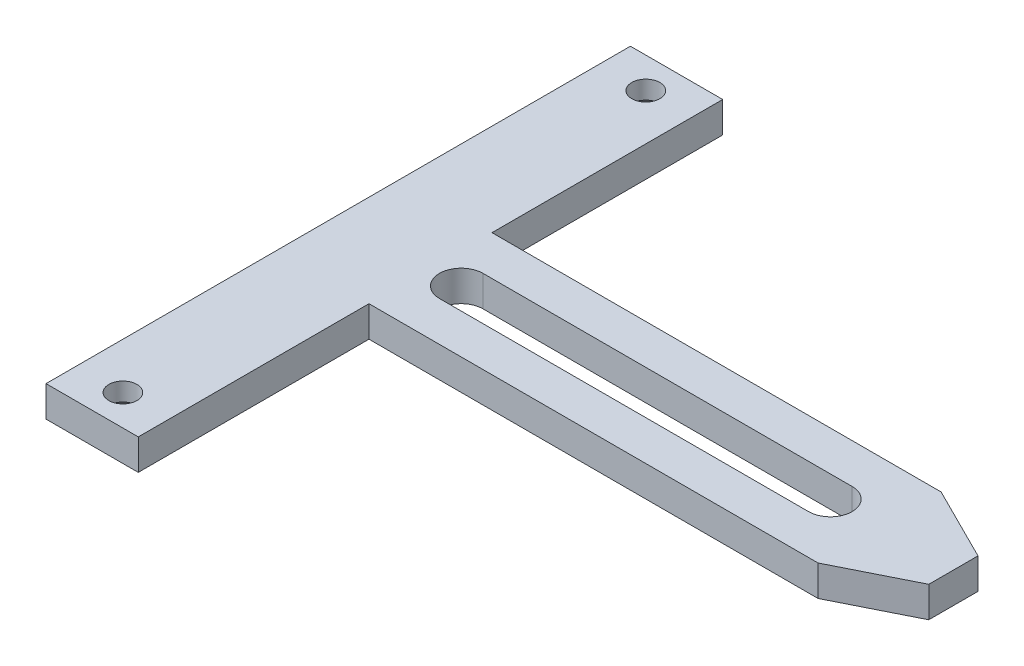
SolidWorks part; units mm, degrees
material "6061 Alloy"
ref_plane "Front" through (0, 0, 0) normal (0, 0, 1) x (1, 0, 0)
ref_plane "Top" through (0, 0, 0) normal (0, 1, 0) x (1, 0, 0)
ref_plane "Right" through (0, 0, 0) normal (1, 0, 0) x (0, 0, -1)
sketch "Sketch2" plane through (0, 0, 0) normal (0, 1, 0) x (1, 0, 0)
  line L1 (-31.75, -30.1625) -> (31.75, -30.1625)
  line L2 (-31.75, -30.1625) -> (-31.75, 30.1625)
  line L3 (-31.75, 30.1625) -> (31.75, 30.1625)
  line L4 (31.75, -30.1625) -> (31.75, 30.1625)
  line L5 (-31.75, -30.1625) -> (31.75, 30.1625) construction
  line L6 (-31.75, 30.1625) -> (31.75, -30.1625) construction
  point P0 (0, 0)
  dimension "D1" = 60.325
  dimension "D2" = 63.5
extrude "Boss-Extrude1" add sketch "Sketch2" along normal mid plane 3.175 contours L3 L4 L1 L2
sketch "Sketch4" plane through (0, 1.5875, 0) normal (0, 1, 0) x (1, 0, 0)
  line L0 (31.75, 2.54) -> (31.75, -2.54) construction
  line L3 (-31.75, -30.1625) -> (31.75, -30.1625) construction
  line L4 (-22.225, -30.1625) -> (31.75, -30.1625)
  line L5 (31.75, -30.1625) -> (31.75, -2.54)
  line L6 (31.75, -30.1625) -> (31.75, 30.1625) construction
  line L7 (-50, 0) -> (50, 0) construction
  line L8 (31.75, 2.54) -> (24.13, 6.35)
  line L10 (-31.75, 30.1625) -> (31.75, 30.1625) construction
  line L11 (31.75, -2.54) -> (24.13, -6.35)
  line L12 (24.13, -6.35) -> (-22.225, -6.35)
  line L13 (24.13, 6.35) -> (-22.225, 6.35)
  line L15 (-22.225, 30.1625) -> (31.75, 30.1625)
  line L16 (31.75, 30.1625) -> (31.75, 2.54)
  line L17 (-22.225, 30.1625) -> (-22.225, 6.35)
  line L18 (-22.225, -30.1625) -> (-22.225, -6.35)
  line L19 (-31.75, -30.1625) -> (-31.75, 30.1625) construction
  point P10 (31.75, 0)
  dimension "D1" = 5.08
  dimension "D2" = 7.62
  dimension "D3" = 12.7
  dimension "D4" = 9.525
extrude "Cut-Extrude1" cut sketch "Sketch4" against normal up to next
sketch "Sketch5" plane through (0, 1.5875, 0) normal (0, 1, 0) x (1, 0, 0)
  line L0 (-19.05, 0) -> (19.05, 0) construction
  line L1 (-50, 0) -> (50, 0) construction
  line L2 (-19.05, 2.2479) -> (19.05, 2.2479)
  line L3 (-19.05, -2.2479) -> (19.05, -2.2479)
  line L5 (31.75, -2.54) -> (31.75, 2.54) construction
  arc A0 (-19.05, 2.2479) -> (-19.05, -2.2479) centre (-19.05, 0) ccw
  arc A1 (19.05, -2.2479) -> (19.05, 2.2479) centre (19.05, 0) ccw
  point P5 (0, 0)
  dimension "D1" = 4.4958
  dimension "D2" = 38.1
  dimension "D3" = 12.7
extrude "Cut-Extrude2" cut sketch "Sketch5" against normal up to next contours L2 A1 L3 A0
sketch "Sketch6" plane through (0, -1.5875, 0) normal (0, 1, 0) x (1, 0, 0)
  line L0 (-31.75, -30.1625) -> (-22.225, -30.1625) construction
  point P0 (-26.9875, -26.9875)
  point P3 (-26.9875, -30.1625)
  dimension "D1" = 3.175
hole_wizard "CSK for M2.5 Flat Head Machine Screw1" positions "Sketch7" profile "Sketch8" countersink size "M2.5" standard "ANSI Metric" end condition up to next
sketch "Sketch7" plane through (0, -1.5875, 0) normal (0, 1, 0) x (1, 0, 0)
  point P0 (-26.9875, -26.9875)
sketch "Sketch8" plane through (-26.9875, -1.5875, 26.9875) normal (1, 0, 0) x (0, 0, -1)
  line L0 (0, 0) -> (0, 3.175)
  line L1 (0, 3.175) -> (1.45, 3.175)
  line L2 (1.45, 3.175) -> (1.45, 1.3)
  line L3 (1.45, 1.3) -> (2.75, 0)
  line L5 (2.75, 0) -> (0, 0)
  line L6 (-1.45, 1.3) -> (-2.75, 0) construction
  line L11 (0, -6.35) -> (0, 107.95) construction
  dimension "Thru Hole Dia." = 2.9
  dimension "Thru Hole Depth" = 3.175
  dimension "Near C'Sink Dia." = 5.5
  dimension "Near C'Sink Angle" = 90
mirror "Mirror1" about plane through (0, 0, 0) normal (0, 0, 1) of "CSK for M2.5 Flat Head Machine Screw1"
